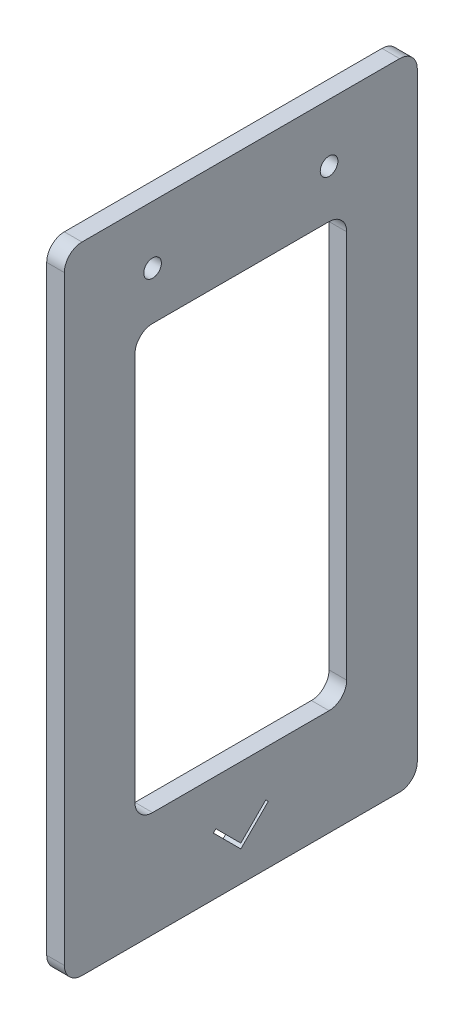
SolidWorks part; units mm, degrees
material "Balsa"
ref_plane "Front Plane" through (0, 0, 0) normal (0, 0, 1) x (1, 0, 0)
ref_plane "Top Plane" through (0, 0, 0) normal (0, 1, 0) x (1, 0, 0)
ref_plane "Right Plane" through (0, 0, 0) normal (1, 0, 0) x (0, 0, -1)
sketch "Sketch3" plane through (0, 0, 0) normal (1, 0, 0) x (0, 0, -1)
  line L0 (-31.75, -76.2) -> (31.75, -76.2)
  line L1 (-57.15, -114.3) -> (57.15, -114.3)
  line L2 (-63.5, -107.95) -> (-63.5, 107.95)
  line L3 (-57.15, 114.3) -> (57.15, 114.3)
  line L4 (63.5, -107.95) -> (63.5, 107.95)
  line L5 (-63.5, -114.3) -> (63.5, 114.3) construction
  line L6 (-63.5, 114.3) -> (63.5, -114.3) construction
  line L8 (-38.1, -69.85) -> (-38.1, 69.85)
  line L9 (-31.75, 76.2) -> (31.75, 76.2)
  line L11 (0, 0) -> (38.1, 76.2) construction
  line L12 (-38.1, 76.2) -> (0, 0) construction
  line L13 (38.1, -69.85) -> (38.1, 69.85)
  arc A0 (-57.15, -114.3) -> (-63.5, -107.95) centre (-57.15, -107.95) cw
  arc A1 (63.5, -107.95) -> (57.15, -114.3) centre (57.15, -107.95) cw
  arc A2 (63.5, 107.95) -> (57.15, 114.3) centre (57.15, 107.95) ccw
  arc A3 (-63.5, 107.95) -> (-57.15, 114.3) centre (-57.15, 107.95) cw
  arc A4 (31.75, -76.2) -> (38.1, -69.85) centre (31.75, -69.85) ccw
  arc A5 (-31.75, -76.2) -> (-38.1, -69.85) centre (-31.75, -69.85) cw
  arc A6 (31.75, 76.2) -> (38.1, 69.85) centre (31.75, 69.85) cw
  arc A7 (-38.1, 69.85) -> (-31.75, 76.2) centre (-31.75, 69.85) cw
  point P0 (0, 0)
  point P6 (0, 0)
  point P26 (38.1, -76.2)
  dimension "D7" = 6.35
  dimension "D8" = 6.35
  dimension "D1" = 228.6
  dimension "D2" = 127
  dimension "D3" = 76.2
  dimension "D4" = 152.4
  dimension "D5" = 38.1
  dimension "D6" = 25.4
extrude "Boss-Extrude2" add sketch "Sketch3" along normal blind 6.35
sketch "Sketch4" plane through (6.35, 0, 0) normal (1, 0, 0) x (0, 0, -1)
  line L0 (0, -101.6) -> (-8.9803, -92.6197)
  line L5 (0, -99.8039) -> (-8.9803, -90.8237) construction
  line L6 (-8.9803, -90.8237) -> (-9.8783, -91.7217) construction
  line L7 (-8.9803, -92.6197) -> (-9.8783, -93.5178)
  line L8 (-9.8783, -91.7217) -> (0, -101.6) construction
  line L9 (0, -101.6) -> (9.8783, -91.7217) construction
  line L10 (9.8783, -91.7217) -> (8.9803, -90.8237) construction
  line L11 (8.9803, -90.8237) -> (0, -99.8039) construction
  line L12 (0, 3.4925) -> (0, -3.4925) construction
  line L13 (-57.15, -114.3) -> (57.15, -114.3) construction
  line L14 (-9.8783, -93.5178) -> (0, -103.3961)
  line L15 (0, -101.6) -> (8.9803, -92.6197)
  line L16 (8.9803, -92.6197) -> (9.8783, -93.5178)
  line L17 (0, -103.3961) -> (9.8783, -93.5178)
  dimension "D1" = 12.7
  dimension "D2" = 12.7
  dimension "D3" = 1.27
  dimension "D4" = 12.7
  dimension "D5" = 1.27
extrude "Cut-Extrude1" cut sketch "Sketch4" against normal up to next
sketch "Sketch5" plane through (6.35, 0, 0) normal (1, 0, 0) x (0, 0, -1)
  line L0 (-57.15, -114.3) -> (57.15, -114.3) construction
  line L1 (-63.5, 93.472) -> (-31.75, 93.472) construction
  line L2 (-63.5, 107.95) -> (-63.5, -107.95) construction
  line L3 (-31.75, 93.472) -> (31.75, 93.472) construction
  line L4 (-31.75, 93.472) -> (31.75, 93.472) construction
  line L5 (31.75, 93.472) -> (63.5, 93.472) construction
  line L6 (63.5, -107.95) -> (63.5, 107.95) construction
  line L7 (-108.1488, 76.2) -> (105.3076, 76.2) construction
  line L8 (31.75, 76.2) -> (-31.75, 76.2) construction
  line L9 (0, 3.4925) -> (0, -3.4925) construction
  circle A0 centre (-31.75, 93.472) radius 3.175
  circle A1 centre (31.75, 93.472) radius 3.175
  point P16 (0, 93.472)
  dimension "D3" = 6.35
  dimension "D4" = 6.35
  dimension "D1" = 63.5
  dimension "D5" = 207.772
extrude "Cut-Extrude2" cut sketch "Sketch5" against normal through all both and the other way through all
